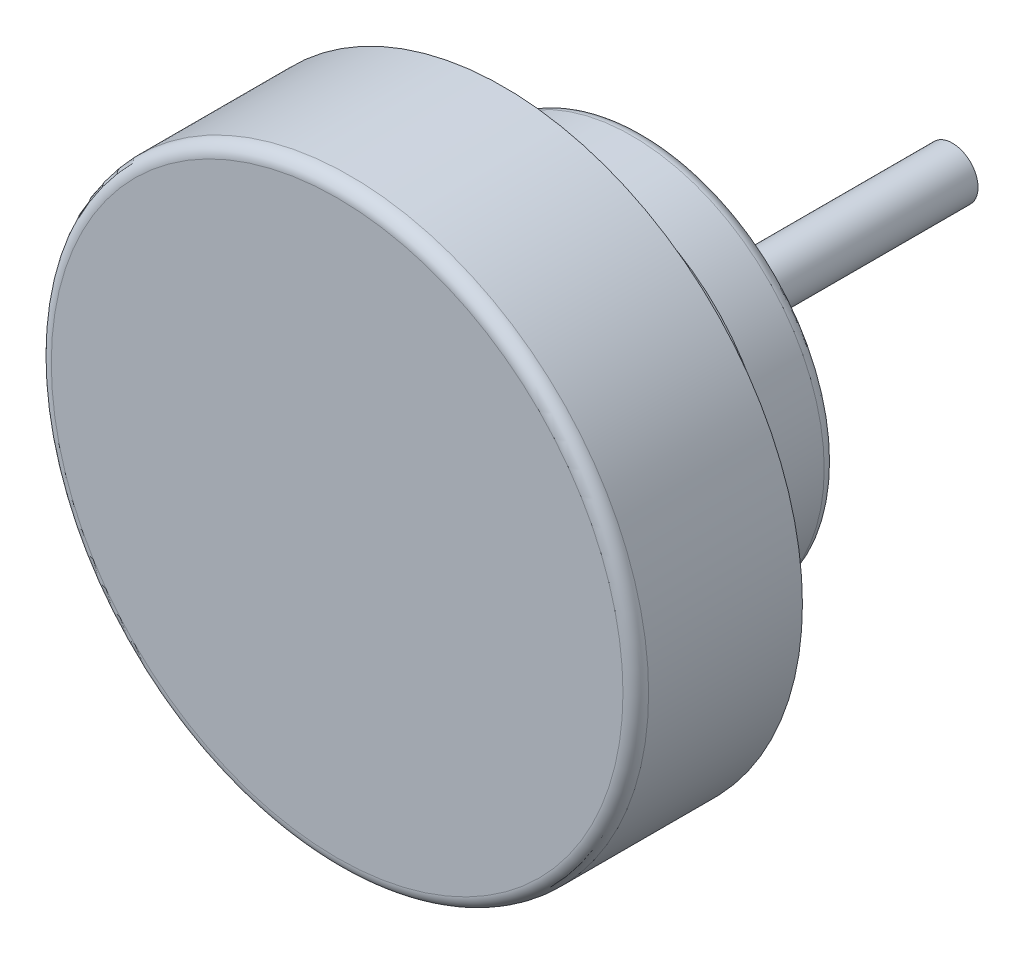
SolidWorks part; units mm, degrees
ref_plane "Front Plane" through (0, 0, 0) normal (0, 0, 1) x (1, 0, 0)
ref_plane "Top Plane" through (0, 0, 0) normal (0, 1, 0) x (1, 0, 0)
ref_plane "Right Plane" through (0, 0, 0) normal (1, 0, 0) x (0, 0, -1)
sketch "Sketch1" plane through (0, 0, 0) normal (0, 0, 1) x (1, 0, 0)
  circle A0 centre (0, 0) radius 11.65
  dimension "D1" = 23.3
extrude "Boss-Extrude1" add sketch "Sketch1" along normal blind 6.5
fillet "Fillet1" radius 0.5 1 edges at (11.65, 0, 6.5)
sketch "Sketch2" plane through (0, 0, 0) normal (0, 0, -1) x (-1, 0, 0)
  circle A0 centre (0, 0) radius 3.25
  dimension "D1" = 6.5
extrude "Boss-Extrude2" add sketch "Sketch2" along normal blind 3
sketch "Sketch3" plane through (0, 0, -3) normal (0, 0, -1) x (-1, 0, 0)
  circle A0 centre (0, 0) radius 7.5
  dimension "D1" = 15
extrude "Boss-Extrude3" add sketch "Sketch3" along normal blind 2.5
fillet "Fillet2" radius 0.5 1 edges at (-7.5, 0, -5.5)
sketch "Sketch4" plane through (0, 0, -5.5) normal (0, 0, -1) x (-1, 0, 0)
  circle A0 centre (0, 0) radius 1
  dimension "D1" = 2
extrude "Boss-Extrude4" add sketch "Sketch4" along normal blind 12
sketch "Sketch5" plane through (0, 0, -5.5) normal (0, 0, -1) x (-1, 0, 0)
  line L0 (0, 0) -> (0, 5.25) construction
  line L1 (0, 0) -> (-4.5466, -2.625) construction
  line L2 (0, 0) -> (4.5466, -2.625) construction
  circle A1 centre (4.5466, -2.625) radius 1
  circle A2 centre (0, 5.25) radius 1
  circle A3 centre (-4.5466, -2.625) radius 1
  dimension "D4" = 2
  dimension "D5" = 2
  dimension "D6" = 2
  dimension "D2" = 120
  dimension "D3" = 120
extrude "Cut-Extrude1" cut sketch "Sketch5" against normal up to next
